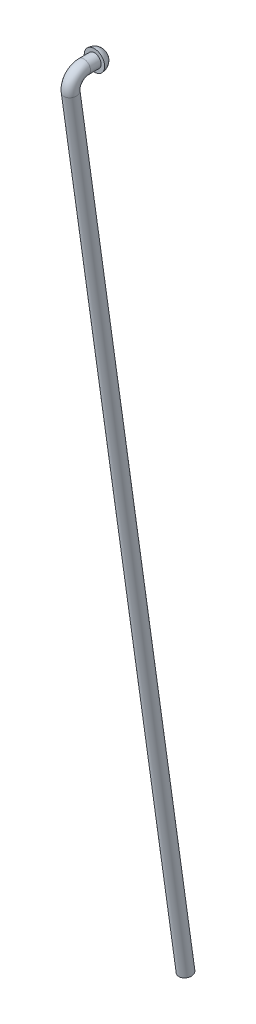
SolidWorks part; units mm, degrees
material "Alloy Steel"
ref_plane "Front Plane" through (0, 0, 0) normal (0, 0, 1) x (1, 0, 0)
ref_plane "Top Plane" through (0, 0, 0) normal (0, 1, 0) x (1, 0, 0)
ref_plane "Right Plane" through (0, 0, 0) normal (1, 0, 0) x (0, 0, -1)
sketch "Sketch1" plane through (0, 0, 0) normal (1, 0, 0) x (0, 0, -1)
  line L0 (5.84, 42.385) -> (3.4499, 42.385)
  line L1 (0.4789, 38.9685) -> (26.3494, -145.5771)
  arc A0 (3.4499, 42.385) -> (0.4789, 38.9685) centre (3.4499, 39.385) ccw
  point P5 (0, 42.385)
  dimension "D4" = 3
  dimension "D1" = 5.84
  dimension "D2" = 82.02
  dimension "D3" = 189.8
ref_plane "Plane1" through (0, 0, -5.84) normal (0, 0, 1) x (1, 0, 0)
sketch "Sketch2" plane through (0, 0, -5.84) normal (0, 0, 1) x (1, 0, 0)
  circle A0 centre (0, 42.385) radius 1.5
  dimension "D1" = 3
sweep "Sweep1" add profiles "Sketch2" path "Sketch1"
sketch "Sketch3" plane through (0, 0, 0) normal (1, 0, 0) x (0, 0, -1)
  line L0 (5.84, 42.385) -> (5.84, 44.685)
  line L1 (5.84, 40.885) -> (5.84, 43.885) construction
  line L2 (8.14, 42.385) -> (5.84, 42.385)
  arc A0 (5.84, 44.685) -> (8.14, 42.385) centre (5.84, 42.385) cw
  dimension "D1" = 2.3
revolve "Revolve1" add sketch "Sketch3" angle 360 about L2
